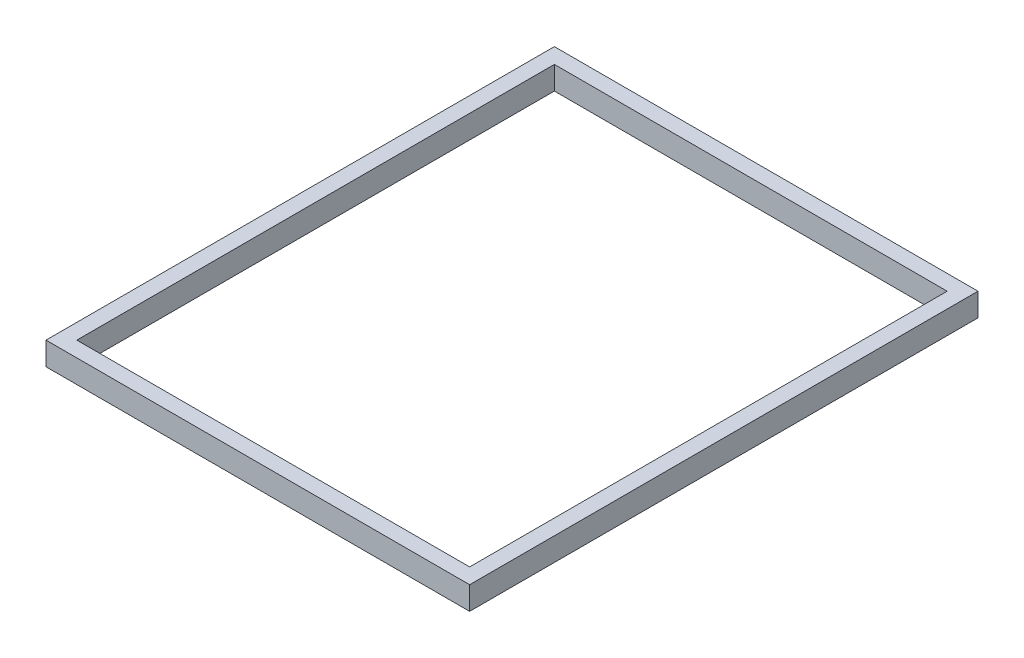
SolidWorks part; units mm, degrees
ref_plane "Front Plane" through (0, 0, 0) normal (0, 0, 1) x (1, 0, 0)
ref_plane "Top Plane" through (0, 0, 0) normal (0, 1, 0) x (1, 0, 0)
ref_plane "Right Plane" through (0, 0, 0) normal (1, 0, 0) x (0, 0, -1)
sketch "Sketch1" plane through (0, 0, 0) normal (0, 1, 0) x (1, 0, 0)
  line L0 (-34.925, -41.91) -> (34.925, -41.91)
  line L1 (-34.925, -41.91) -> (-34.925, 41.91)
  line L2 (-34.925, 41.91) -> (34.925, 41.91)
  line L3 (34.925, -41.91) -> (34.925, 41.91)
  line L4 (-32.385, -39.37) -> (32.385, -39.37)
  line L5 (-32.385, -39.37) -> (-32.385, 39.37)
  line L6 (-32.385, 39.37) -> (32.385, 39.37)
  line L7 (32.385, -39.37) -> (32.385, 39.37)
extrude "Boss-Extrude1" add sketch "Sketch1" along normal blind 3.81
